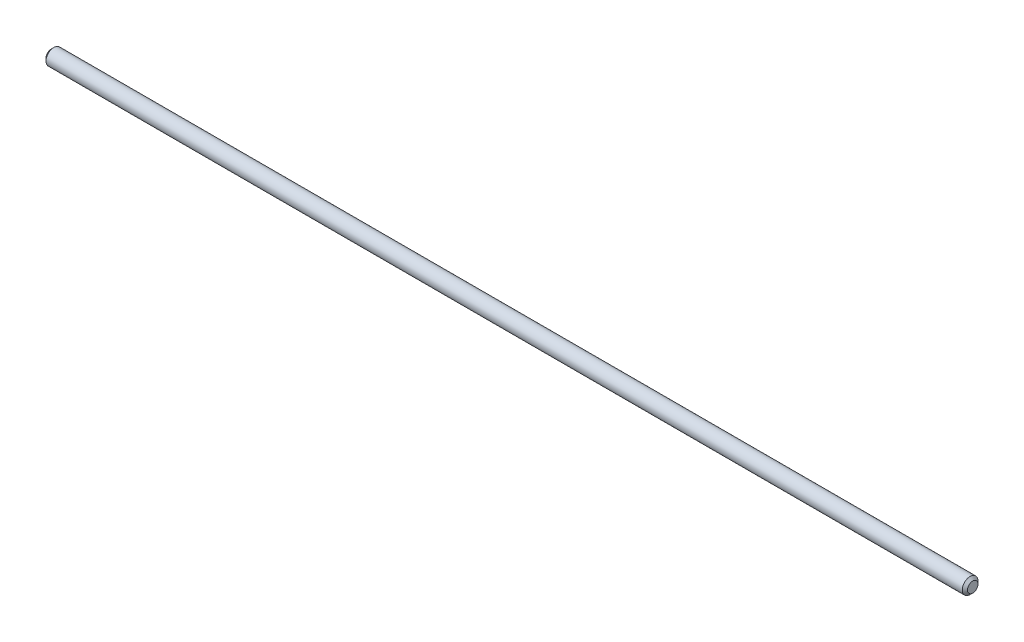
SolidWorks part; units mm, degrees
ref_plane "Front Plane" through (0, 0, 0) normal (0, 0, 1) x (1, 0, 0)
ref_plane "Top Plane" through (0, 0, 0) normal (0, 1, 0) x (1, 0, 0)
ref_plane "Right Plane" through (0, 0, 0) normal (1, 0, 0) x (0, 0, -1)
sketch "Sketch2" plane through (0, 0, 0) normal (1, 0, 0) x (0, 0, -1)
  circle A0 centre (0, 0) radius 1.5
  dimension "D1" = 3
extrude "Boss-Extrude1" add sketch "Sketch2" along normal blind 175.5
chamfer "Chamfer1" distance 0.5 angle 45 2 edges at (0, 0, -1.5) (175.5, 0, -1.5)
